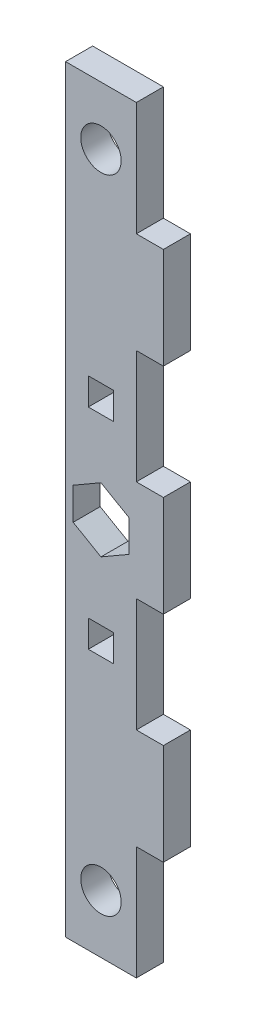
SolidWorks part; units mm, degrees
ref_plane "Front Plane" through (0, 0, 0) normal (0, 0, 1) x (1, 0, 0)
ref_plane "Top Plane" through (0, 0, 0) normal (0, 1, 0) x (1, 0, 0)
ref_plane "Right Plane" through (0, 0, 0) normal (1, 0, 0) x (0, 0, -1)
sketch "Model" plane through (0, 0, 0) normal (0, 0, 1) x (1, 0, 0)
  line L242 (4.5, 51.575) -> (9.5, 51.575)
  line L243 (9.5, 51.575) -> (9.5, 56.925)
  line L244 (9.5, 56.925) -> (4.5, 56.925)
  line L245 (4.5, 56.925) -> (4.5, 51.575)
  line L246 (14, 127.5) -> (14, 150)
  line L247 (19.35, 127.5) -> (14, 127.5)
  line L248 (19.35, 107.5) -> (19.35, 127.5)
  line L249 (14, 107.5) -> (19.35, 107.5)
  line L250 (14, 85) -> (14, 107.5)
  line L251 (19.35, 85) -> (14, 85)
  line L252 (19.35, 65) -> (19.35, 85)
  line L253 (14, 65) -> (19.35, 65)
  line L254 (14, 42.5) -> (14, 65)
  line L255 (19.35, 42.5) -> (14, 42.5)
  line L256 (19.35, 22.5) -> (19.35, 42.5)
  line L257 (14, 22.5) -> (19.35, 22.5)
  line L258 (14, 0) -> (14, 22.5)
  line L259 (0, 0) -> (14, 0)
  line L260 (0, 150) -> (0, 0)
  line L261 (14, 150) -> (0, 150)
  line L262 (9.5, 98.425) -> (4.5, 98.425)
  line L263 (4.5, 98.425) -> (4.5, 93.075)
  line L264 (4.5, 93.075) -> (9.5, 93.075)
  line L265 (9.5, 93.075) -> (9.5, 98.425)
  line L266 (1.5, 71.8246) -> (7, 68.6492)
  line L267 (7, 68.6492) -> (12.5, 71.8246)
  line L268 (12.5, 71.8246) -> (12.5, 78.1754)
  line L269 (12.5, 78.1754) -> (7, 81.3509)
  line L270 (7, 81.3509) -> (1.5, 78.1754)
  line L271 (1.5, 78.1754) -> (1.5, 71.8246)
  circle A32 centre (7, 11.5) radius 4
  circle A33 centre (7, 138.5) radius 4
extrude "Boss-Extrude1" add sketch "Model" along normal blind 5.35
